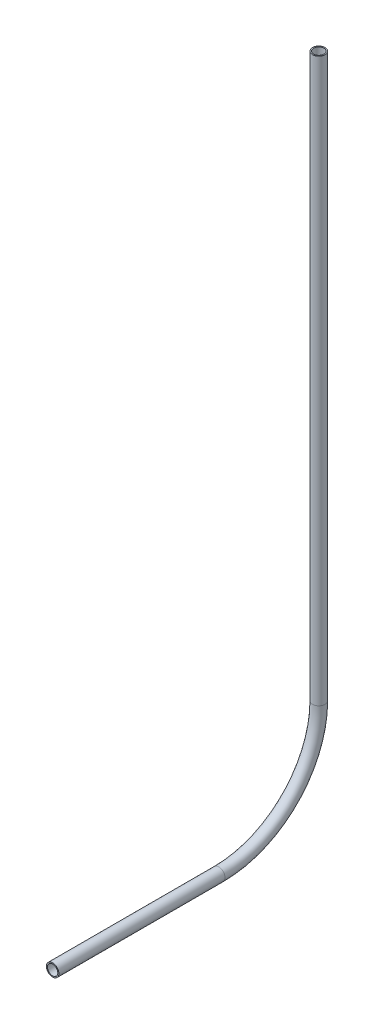
SolidWorks part; units mm, degrees
ref_plane "Front Plane" through (0, 0, 0) normal (0, 0, 1) x (1, 0, 0)
ref_plane "Top Plane" through (0, 0, 0) normal (0, 1, 0) x (1, 0, 0)
ref_plane "Right Plane" through (0, 0, 0) normal (1, 0, 0) x (0, 0, -1)
sketch "Sketch1" plane through (0, 0, 0) normal (1, 0, 0) x (0, 0, -1)
  line L0 (-142.2963, 164.303) -> (-57.921, 164.303)
  line L1 (-7.121, 215.103) -> (-7.121, 500.8232)
  arc A0 (-57.921, 164.303) -> (-7.121, 215.103) centre (-57.921, 215.103) ccw
  dimension "D1" = 50.8
other "Pipe 0.5 SCH 40(1)"
ref_plane "Plane1" through (0, 164.303, 142.2963) normal (0, 0, -1) x (0, 1, 0)
sketch "Sketch11" plane through (0, 164.303, 142.2963) normal (0, 0, -1) x (0, 1, 0)
  circle A0 centre (0, 0) radius 3.175
  circle A1 centre (0, 0) radius 2.6162
  point P5 (0, 0)
  dimension "In_dia" = 6.35
  dimension "Out_dia" = 5.2324
